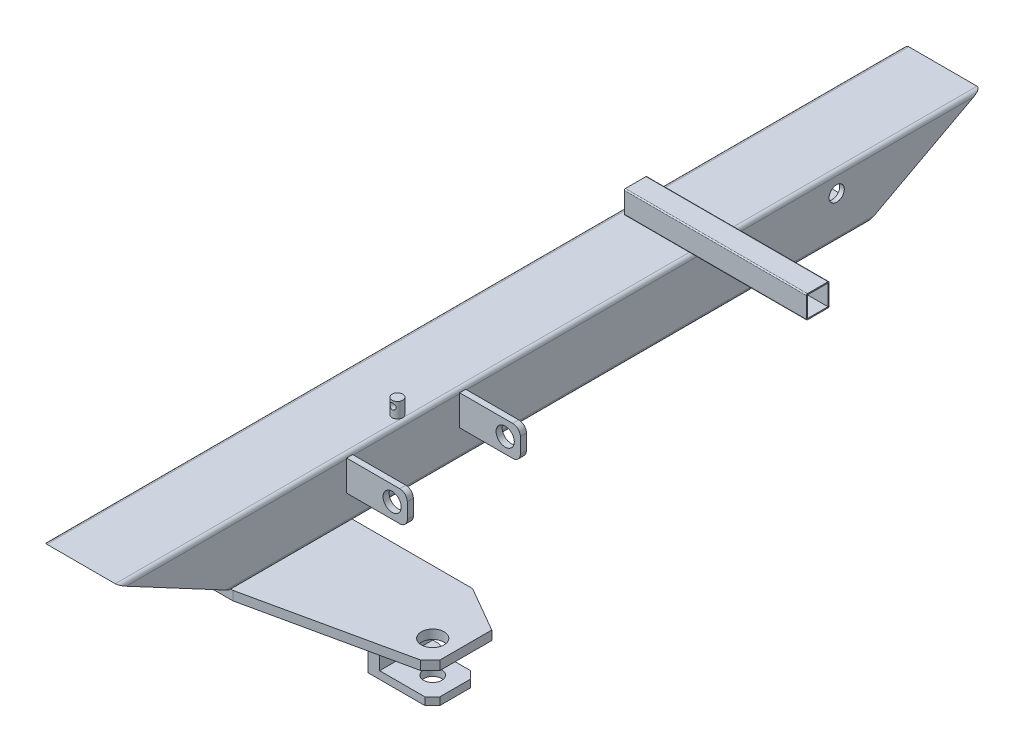
SolidWorks part; units mm, degrees
material "Structural Steel"
ref_plane "Piano frontale" through (0, 0, 0) normal (0, 0, 1) x (1, 0, 0)
ref_plane "Piano superiore" through (0, 0, 0) normal (0, 1, 0) x (1, 0, 0)
ref_plane "Piano destro" through (0, 0, 0) normal (1, 0, 0) x (0, 0, -1)
sketch "Schizzo1" plane through (0, 0, 0) normal (0, 0, 1) x (1, 0, 0)
  line L1 (5, 0) -> (95, 0)
  line L2 (0, 5) -> (0, 75)
  line L3 (5, 80) -> (95, 80)
  line L4 (100, 5) -> (100, 75)
  arc A0 (0, 75) -> (5, 80) centre (5, 75) cw
  arc A1 (95, 80) -> (100, 75) centre (95, 75) cw
  arc A2 (95, 0) -> (100, 5) centre (95, 5) ccw
  arc A3 (5, 0) -> (0, 5) centre (5, 5) cw
  point P7 (0, 80)
  point P12 (100, 0)
  point P15 (0, 0)
  dimension "D3" = 5
  dimension "D1" = 100
  dimension "D2" = 80
extrude "Estrusione-Sottile1" add sketch "Schizzo1" along normal blind 1200 thin
sketch "Schizzo2" plane through (100, 0, 0) normal (1, 0, 0) x (0, 0, -1)
  line L0 (-1050, 181.1521) -> (-1050, -156.5272) construction
  line L1 (-1200, 5) -> (-1200, 75) construction
  line L2 (-214, 163.6994) -> (-214, -110.5533) construction
  line L3 (-1200, 80) -> (-1050, 0)
  line L4 (-1050, 0) -> (-1200, 0)
  line L5 (-1200, 0) -> (-1200, 80)
  line L6 (-64, 157.8086) -> (-64, -67.0058) construction
  line L7 (-64, 80) -> (-214, 0)
  line L8 (-1200, 80) -> (0, 80) construction
  line L9 (-1200, 0) -> (0, 0) construction
  line L10 (-214, 0) -> (0, 0)
  line L11 (0, 0) -> (0, 80)
  line L12 (0, 80) -> (-64, 80)
  dimension "D1" = 150
  dimension "D2" = 836
  dimension "D3" = 150
extrude "Estrusione1" cut sketch "Schizzo2" against normal through all
sketch "Schizzo4" plane through (0, 0, 0) normal (0, -1, 0) x (1, 0, 0)
  line L0 (5, 1050) -> (100, 1050)
  line L1 (100, 1059.375) -> (100, 204.625) construction
  line L2 (100, 1050) -> (316, 1003)
  line L3 (316, 1003) -> (316, 890)
  line L4 (316, 890) -> (95, 890)
  line L5 (95, 1050) -> (95, 214) construction
  line L6 (95, 890) -> (5, 890)
  line L7 (5, 1050) -> (5, 214) construction
  line L8 (5, 890) -> (5, 1050)
  circle A0 centre (286.5, 973) radius 15
  dimension "D2" = 30
  dimension "D1" = 216
  dimension "D3" = 186.5
  dimension "D4" = 77
  dimension "D5" = 47
  dimension "D6" = 160
  dimension "D7" = 113
extrude "Estrusione3" add sketch "Schizzo4" along normal blind 12
sketch "Schizzo5" plane through (0, -12, 0) normal (0, -1, 0) x (1, 0, 0)
  line L1 (231.5, 1003) -> (246.5, 1003)
  line L2 (231.5, 1003) -> (231.5, 933)
  line L3 (231.5, 933) -> (246.5, 933)
  line L4 (246.5, 1003) -> (246.5, 933)
  circle A0 centre (286.5, 973) radius 15 construction
  dimension "D1" = 40
  dimension "D3" = 30
  dimension "D4" = 40
  dimension "D2" = 15
extrude "Estrusione4" add sketch "Schizzo5" along normal blind 30
sketch "Schizzo7" plane through (0, -42, 0) normal (0, -1, 0) x (1, 0, 0)
  line L0 (316, 890) -> (316, 1003) construction
  line L1 (231.5, 1003) -> (316, 1003)
  line L2 (231.5, 1003) -> (231.5, 933)
  line L3 (231.5, 933) -> (261.5, 933)
  line L4 (316, 1003) -> (316, 943)
  line L5 (261.5, 933) -> (261.5, 943)
  line L6 (261.5, 943) -> (316, 943)
  dimension "D1" = 60
  dimension "D2" = 30
extrude "Estrusione5" add sketch "Schizzo7" along normal blind 10
sketch "Schizzo8" plane through (0, 0, 0) normal (0, 1, 0) x (1, 0, 0)
  circle A0 centre (286.5, -973) radius 12
  dimension "D1" = 24
extrude "Estrusione6" cut sketch "Schizzo8" against normal through all
chamfer "Smusso1" distance 60 angle 30 1 edges at (316, -6, 890)
chamfer "Smusso2" distance 10 angle 45 3 edges at (316, -6, 1003) (316, -47, 1003) (316, -47, 943)
fillet "Raccordo1" radius 8 1 edges at (261.5, -47, 933)
sketch "Schizzo9" plane through (100, 0, 0) normal (1, 0, 0) x (0, 0, -1)
  line L1 (-1200, 80) -> (-64, 80) construction
  circle A0 centre (-254, 55) radius 6
  dimension "D1" = 12
  dimension "D3" = 40
  dimension "D2" = 25
extrude "Estrusione7" cut sketch "Schizzo9" against normal through all
sketch "Schizzo10" plane through (100, 0, 0) normal (1, 0, 0) x (0, 0, -1)
  circle A0 centre (-254, 55) radius 10
  dimension "D1" = 20
extrude "Estrusione8" cut sketch "Schizzo10" against normal blind 10
sketch "Schizzo11" plane through (100, 0, 0) normal (1, 0, 0) x (0, 0, -1)
  line L0 (-1200, 80) -> (-64, 80) construction
  line L1 (-415.5, 80) -> (-442.5, 80)
  line L2 (-414, 81.5) -> (-414, 108.5)
  line L3 (-415.5, 110) -> (-442.5, 110)
  line L4 (-444, 81.5) -> (-444, 108.5)
  circle A0 centre (-254, 55) radius 6 construction
  arc A1 (-442.5, 80) -> (-444, 81.5) centre (-442.5, 81.5) cw
  arc A2 (-415.5, 80) -> (-414, 81.5) centre (-415.5, 81.5) ccw
  arc A3 (-414, 108.5) -> (-415.5, 110) centre (-415.5, 108.5) ccw
  arc A4 (-442.5, 110) -> (-444, 108.5) centre (-442.5, 108.5) ccw
  point P10 (-444, 80)
  point P13 (-414, 80)
  point P16 (-414, 110)
  point P19 (-444, 110)
  dimension "D3" = 160
  dimension "D4" = 1.5
  dimension "D1" = 30
  dimension "D2" = 30
extrude "Estrusione-Sottile2" add sketch "Schizzo11" along normal blind 150 and the other way blind 90 thin
sketch "Schizzo12" plane through (100, 0, 0) normal (1, 0, 0) x (0, 0, -1)
  line L0 (-1200, 80) -> (-442.5, 80) construction
  line L1 (-900, 76) -> (-892, 76)
  line L2 (-900, 76) -> (-900, 36)
  line L3 (-900, 36) -> (-892, 36)
  line L4 (-892, 76) -> (-892, 36)
  dimension "D1" = 8
  dimension "D2" = 40
  dimension "D3" = 4
  dimension "D4" = 300
extrude "Estrusione-Estrusione1" add sketch "Schizzo12" along normal blind 80
sketch "Schizzo13" plane through (0, 0, 892) normal (0, 0, -1) x (-1, 0, 0)
  line L0 (-180, 56) -> (-133.2463, 56) construction
  line L1 (-180, 36) -> (-180, 76) construction
  line L2 (-100, 75) -> (-100, 5) construction
  circle A0 centre (-160, 56) radius 12
  dimension "D1" = 24
  dimension "D2" = 60
extrude "Taglio-Estrusione1" cut sketch "Schizzo13" against normal through all
fillet "Raccordo2" radius 10 2 edges at (180, 36, 896) (180, 76, 896)
pattern_linear "Ripetizione a L1" count 2 spacing 149 along (0, 0, -1) of "Estrusione-Estrusione1", "Taglio-Estrusione1", "Raccordo2"
sketch "Schizzo14" plane through (0, 80, 0) normal (0, 1, 0) x (1, 0, 0)
  line L0 (100, -1190.625) -> (100, -900) construction
  line L1 (95, -1200) -> (5, -1200) construction
  circle A0 centre (88, -821) radius 7
  dimension "D1" = 14
  dimension "D2" = 12
  dimension "D3" = 379
extrude "Estrusione-Estrusione2" add sketch "Schizzo14" along normal blind 20
sketch "Schizzo15" plane through (0, 0, 0) normal (0, 0, 1) x (1, 0, 0)
  line L0 (88, 100) -> (88, 84.534) construction
  line L1 (95, 100) -> (81, 100) construction
  line L2 (95, 80) -> (5, 80) construction
  circle A0 centre (88, 93) radius 4
  dimension "D1" = 8
  dimension "D2" = 13
extrude "Taglio-Estrusione2" cut sketch "Schizzo15" along normal blind 250 from offset 670
